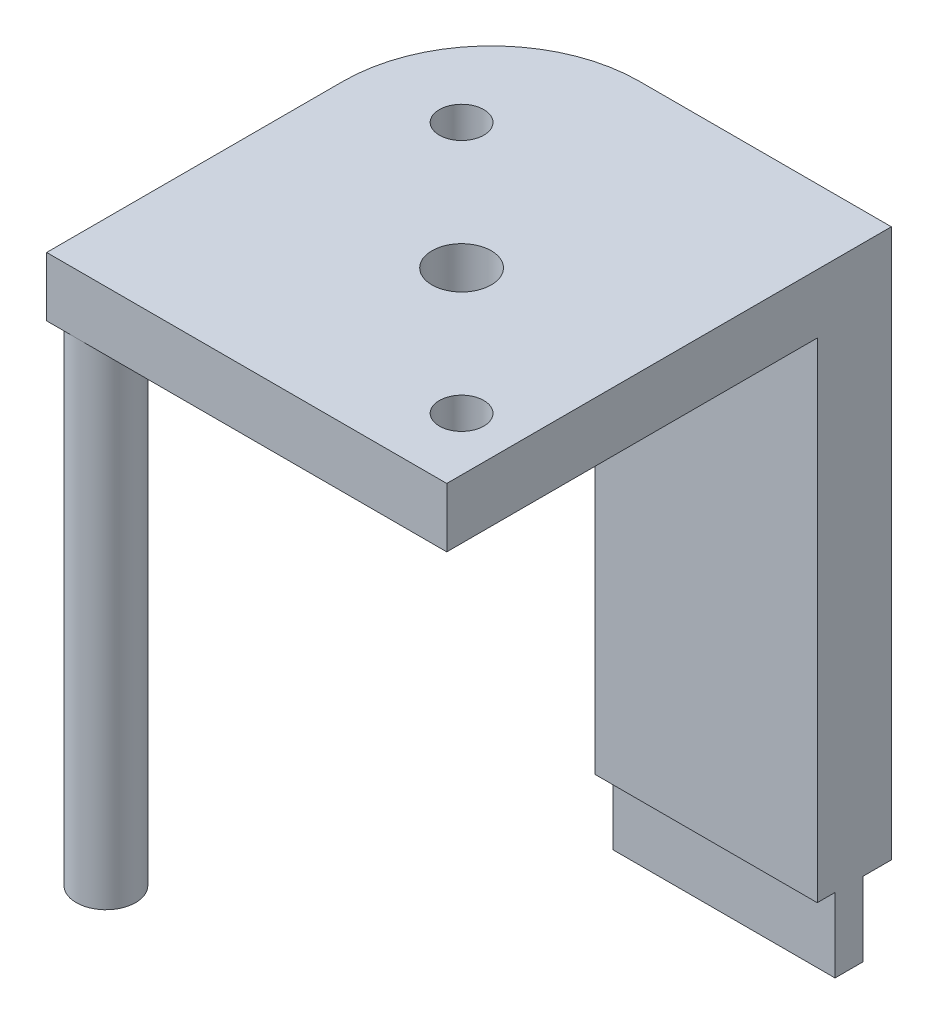
SolidWorks part; units mm, degrees
ref_plane "前视基准面" through (0, 0, 0) normal (0, 0, 1) x (1, 0, 0)
ref_plane "上视基准面" through (0, 0, 0) normal (0, 1, 0) x (1, 0, 0)
ref_plane "右视基准面" through (0, 0, 0) normal (1, 0, 0) x (0, 0, -1)
sketch "草图1" plane through (0, 0, 0) normal (0, 1, 0) x (1, 0, 0)
  line L1 (-3.5, 15) -> (13.5, 15)
  line L2 (-13.5, 5) -> (-13.5, -15)
  line L3 (-13.5, -15) -> (13.5, -15)
  line L4 (13.5, 15) -> (13.5, -15)
  line L5 (-13.5, 15) -> (13.5, -15) construction
  line L6 (-13.5, -15) -> (13.5, 15) construction
  arc A0 (-13.5, 5) -> (-3.5, 15) centre (-3.5, 5) cw
  point P0 (0, 0)
  dimension "D1" = 10
  dimension "D2" = 30
  dimension "D3" = 27
extrude "凸台-拉伸1" add sketch "草图1" along normal blind 37
sketch "草图2" plane through (0, 0, 0) normal (0, 1, 0) x (1, 0, 0)
  line L0 (13.5, 15) -> (-3.5, 15) construction
  line L1 (13.5, -15) -> (-13.5, -15)
  line L2 (13.5, -15) -> (13.5, 15)
  line L3 (13.5, 15) -> (-13.5, 15)
  line L4 (-13.5, -15) -> (-13.5, 15)
  line L5 (13.5, -15) -> (-13.5, 15) construction
  line L6 (13.5, 15) -> (-13.5, -15) construction
  line L7 (-1.5, 15) -> (13.5, 15)
  line L8 (-1.5, 15) -> (-1.5, 10)
  line L9 (-1.5, 10) -> (13.5, 10)
  line L10 (13.5, 15) -> (13.5, 10)
  line L11 (-1.5, 15) -> (13.5, 10) construction
  line L12 (-1.5, 10) -> (13.5, 15) construction
  circle A0 centre (-11.5, -13) radius 2
  point P4 (0, 0)
  point P10 (6, 12.5)
extrude "切除-拉伸1" cut sketch "草图2" along normal offset from surface (33 mm away) 4 contours A0 L1 L2 L9 L8 L3 L4 | A0 L4 L1 up to face at (-1.1142, 37, -1.4142)
sketch "草图3" plane through (0, 0, 0) normal (0, -1, 0) x (1, 0, 0)
  line L0 (-1.5, -10) -> (-1.5, -15) construction
  line L1 (-1.5, -11.2) -> (13.5, -11.2)
  line L2 (-1.5, -11.2) -> (-1.5, -13.1)
  line L3 (-1.5, -13.1) -> (13.5, -13.1)
  line L4 (13.5, -11.2) -> (13.5, -13.1)
  line L5 (-1.5, -11.2) -> (13.5, -13.1) construction
  line L6 (-1.5, -13.1) -> (13.5, -11.2) construction
  line L7 (13.5, -10) -> (13.5, -15) construction
  line L8 (13.5, -15) -> (-1.5, -15) construction
  point P4 (6, -12.15)
  dimension "D1" = 1.9
  dimension "D2" = 1.9
extrude "凸台-拉伸2" add sketch "草图3" along normal blind 5
sketch "草图4" plane through (0, 33, 0) normal (0, -1, 0) x (1, 0, 0)
  line L0 (-13.5, -5) -> (-13.5, 13) construction
  line L1 (13.5, -15) -> (-1.5, -15) construction
  circle A0 centre (1.4, 1.9) radius 2
  dimension "D3" = 4
  dimension "D1" = 14.9
  dimension "D2" = 16.9
extrude "切除-拉伸2" cut sketch "草图4" against normal blind 10
sketch "草图5" plane through (0, 37, 0) normal (0, 1, 0) x (1, 0, 0)
  line L0 (13.5, 15) -> (-3.5, 15) construction
  line L1 (-13.5, 5) -> (-13.5, -15) construction
  line L2 (13.5, -15) -> (13.5, 15) construction
  line L3 (-13.5, -15) -> (13.5, -15) construction
  circle A0 centre (-7.1, 6.6) radius 1.5
  circle A1 centre (9.9, -10.4) radius 1.5
  dimension "D1" = 3
  dimension "D4" = 3
  dimension "D6" = 4.6
  dimension "D2" = 8.4
  dimension "D3" = 6.4
  dimension "D5" = 3.6
extrude "切除-拉伸3" cut sketch "草图5" against normal through all
